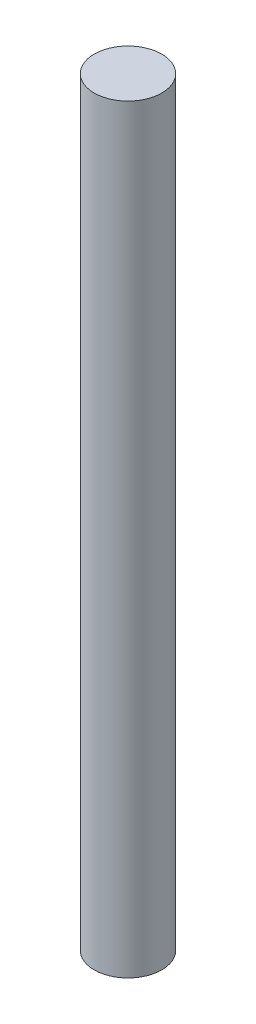
SolidWorks part; units mm, degrees
ref_plane "Front Plane" through (0, 0, 0) normal (0, 0, 1) x (1, 0, 0)
ref_plane "Top Plane" through (0, 0, 0) normal (0, 1, 0) x (1, 0, 0)
ref_plane "Right Plane" through (0, 0, 0) normal (1, 0, 0) x (0, 0, -1)
sketch "Sketch1" plane through (0, 0, 0) normal (0, 1, 0) x (1, 0, 0)
  circle A0 centre (0, 0) radius 1.016
  dimension "D1" = 2.032
extrude "Boss-Extrude1" add sketch "Sketch1" along normal blind 22.86
